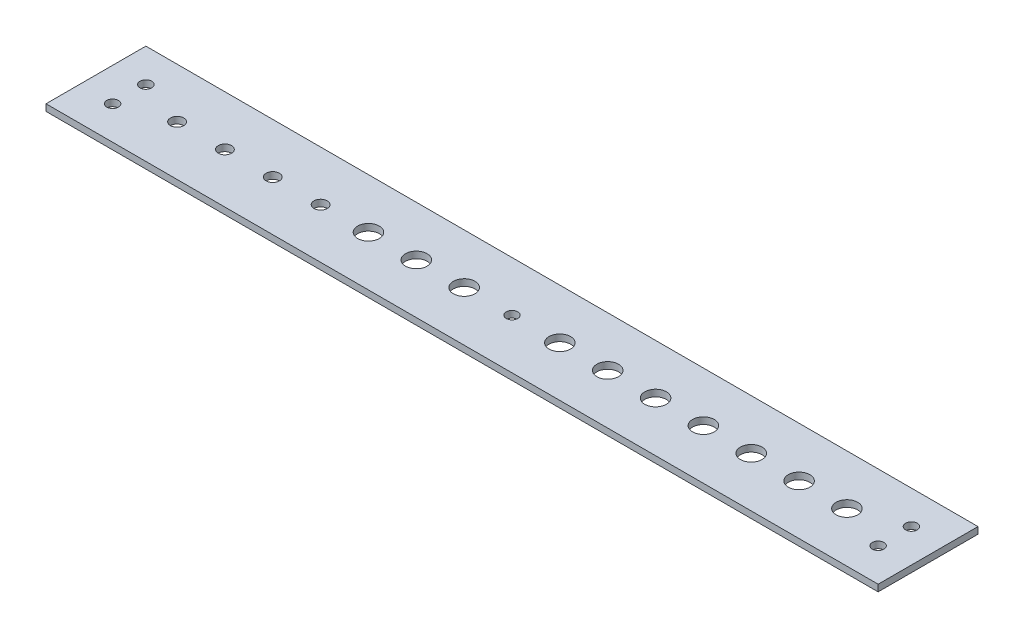
SolidWorks part; units mm, degrees
ref_plane "Front Plane" through (0, 0, 0) normal (0, 0, 1) x (1, 0, 0)
ref_plane "Top Plane" through (0, 0, 0) normal (0, 1, 0) x (1, 0, 0)
ref_plane "Right Plane" through (0, 0, 0) normal (1, 0, 0) x (0, 0, -1)
sketch "Sketch1" plane through (0, 0, 0) normal (0, 1, 0) x (1, 0, 0)
  line L1 (125, -15) -> (-125, -15)
  line L2 (125, -15) -> (125, 15)
  line L3 (125, 15) -> (-125, 15)
  line L4 (-125, -15) -> (-125, 15)
  line L5 (125, -15) -> (-125, 15) construction
  line L6 (125, 15) -> (-125, -15) construction
  circle A0 centre (-115, 5) radius 1.75
  circle A1 centre (-115, -5) radius 1.75
  circle A2 centre (0, 0) radius 1.75
  circle A3 centre (115, 5) radius 1.75
  circle A4 centre (115, -5) radius 1.75
  circle A5 centre (-100.625, 0) radius 2
  circle A6 centre (-71.875, 0) radius 2
  circle A7 centre (-57.5, 0) radius 2
  circle A8 centre (14.375, 0) radius 3.25
  circle A9 centre (43.125, 0) radius 3.25
  circle A10 centre (57.5, 0) radius 3.25
  circle A11 centre (71.875, 0) radius 3.25
  circle A12 centre (86.25, 0) radius 3.25
  circle A13 centre (100.625, 0) radius 3.25
  circle A14 centre (-43.125, 0) radius 3.25
  circle A15 centre (-86.25, 0) radius 2
  circle A16 centre (-28.75, 0) radius 3.25
  circle A17 centre (-14.375, 0) radius 3.25
  circle A18 centre (28.75, 0) radius 3.25
  point P0 (0, 0)
  dimension "D3" = 3.5
  dimension "D8" = 4
  dimension "D24" = 6.5
  dimension "D1" = 250
  dimension "D2" = 30
  dimension "D4" = 10
  dimension "D5" = 10
  dimension "D6" = 10
  dimension "D7" = 10
  dimension "D9" = 14.375
  dimension "D10" = 14.375
  dimension "D11" = 14.375
  dimension "D12" = 14.375
  dimension "D13" = 14.375
  dimension "D14" = 14.375
  dimension "D15" = 14.375
  dimension "D16" = 14.375
  dimension "D17" = 14.375
  dimension "D18" = 14.375
  dimension "D19" = 14.375
  dimension "D20" = 14.375
  dimension "D21" = 14.375
  dimension "D22" = 14.375
extrude "Boss-Extrude1" add sketch "Sketch1" along normal blind 2
